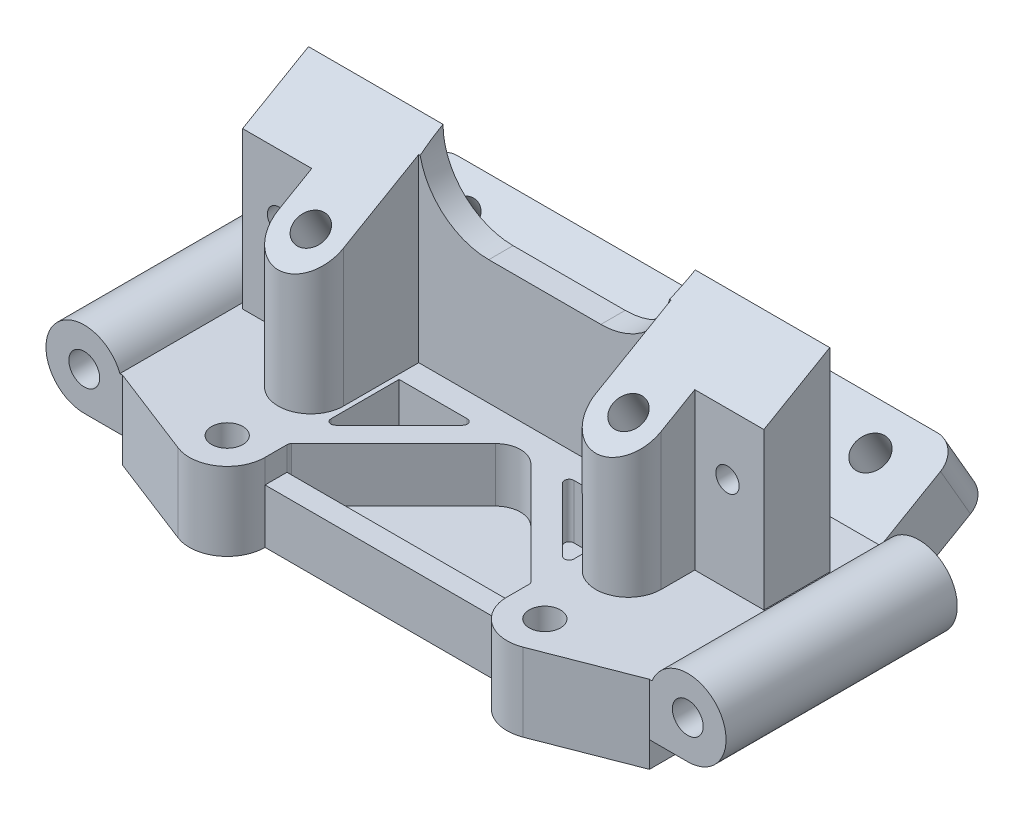
SolidWorks part; units mm, degrees
ref_plane "Front Plane" through (0, 0, 0) normal (0, 0, 1) x (1, 0, 0)
ref_plane "Top Plane" through (0, 0, 0) normal (0, 1, 0) x (1, 0, 0)
ref_plane "Right Plane" through (0, 0, 0) normal (1, 0, 0) x (0, 0, -1)
sketch "Sketch1" plane through (0, 0, 0) normal (0, 1, 0) x (1, 0, 0)
  line L0 (28.2, 0) -> (0, 0)
  line L1 (28.2, 0) -> (28.2, -24.75)
  line L2 (28.2, -24.75) -> (18.4645, -28.5259)
  line L3 (12.95, -24.75) -> (0, -24.75)
  line L4 (0, -24.75) -> (0, 0)
  arc A0 (12.95, -24.75) -> (18.4645, -28.5259) centre (17, -24.75) ccw
  circle A1 centre (17, -24.75) radius 1.675
  circle A2 centre (17, -9.75) radius 1.675
  point P9 (17, -28.8)
  point P11 (0, 0)
  dimension "D6" = 3.35
  dimension "D1" = 17
  dimension "D2" = 28.2
  dimension "D3" = 28.8
  dimension "D4" = 24.75
  dimension "D5" = 15
extrude "Boss-Extrude1" add sketch "Sketch1" along normal blind 8.35
sketch "Sketch2" plane through (0, 0, 0) normal (0, 0, -1) x (-1, 0, 0)
  line L0 (-28.2, 2.75) -> (-32.3, 2.75)
  line L1 (-28.2, 8.35) -> (-28.2, 0) construction
  line L2 (-28.2, 0) -> (0, 0) construction
  line L3 (-28.2, 2.75) -> (-28.2, 8.35)
  line L4 (-28.2, 8.35) -> (-28.4842, 8.35)
  arc A0 (-28.4842, 8.35) -> (-32.3, 2.75) centre (-32.3, 6.85) ccw
  circle A1 centre (-32.3, 6.85) radius 1.65
  point P5 (-36.4, 6.85)
  line M8 (-28.2, 8.35) -> (-28.2, 0)
  dimension "D1" = 8.2
  dimension "D3" = 3.3
  dimension "D2" = 2.75
extrude "Boss-Extrude2" add sketch "Sketch2" against normal up to vertex (24.75 mm away) contours L4 A0 L0 A1 M8
sketch "Sketch3" plane through (0, 8.35, 0) normal (0, 1, 0) x (1, 0, 0)
  line L0 (0, 0) -> (0, -24.75) construction
  line L1 (0, -5.15) -> (27.9, -5.15)
  line L2 (0, -5.15) -> (0, -12.2)
  line L3 (0, -12.2) -> (27.9, -12.2)
  line L4 (27.9, -5.15) -> (27.9, -12.2)
  line L5 (17, -12.2) -> (17, -15.8) construction
  line L6 (20.5, -12.2) -> (20.5, -15.8)
  line L7 (28.4842, 0) -> (0, 0) construction
  line L8 (13.5, -12.2) -> (13.5, -15.8)
  line L9 (13.5, -12.2) -> (13.5, -7.75)
  line L10 (13.5, -7.75) -> (0, -7.75)
  line L11 (0, -24.75) -> (12.95, -24.75) construction
  arc A0 (20.5, -12.2) -> (13.5, -12.2) centre (17, -12.2) ccw
  arc A1 (13.5, -15.8) -> (20.5, -15.8) centre (17, -15.8) ccw
  point P10 (17, -14)
  point P15 (17, -24.75)
  point P18 (17, -19.3)
  dimension "D1" = 7.05
  dimension "D2" = 12.2
  dimension "D3" = 27.9
  dimension "D4" = 17
  dimension "D5" = 14.15
  dimension "D6" = 17
  dimension "D7" = 7
extrude "Boss-Extrude3" add sketch "Sketch3" along normal blind 20.8
sketch "Sketch4" plane through (27.9, 0, 0) normal (1, 0, 0) x (0, 0, -1)
  line L0 (-5.15, 29.15) -> (-19.3, 20.9805)
  line L1 (-19.3, 20.9805) -> (-19.3, 29.15)
  line L2 (-19.3, 29.15) -> (-5.15, 29.15)
  line L3 (-19.3, 29.15) -> (-19.3, 8.35) construction
  point P5 (0, 0)
  dimension "D1" = 60
extrude "Cut-Extrude1" cut sketch "Sketch4" against normal through all
sketch "Sketch5" plane through (0, 0, 5.15) normal (0, 0, -1) x (-1, 0, 0)
  line L1 (0, 29.15) -> (-27.9, 29.15) construction
  line L2 (-6, 21.65) -> (0, 21.65)
  line L4 (0, 21.65) -> (0, 29.15)
  line L5 (0, 29.15) -> (-13.5, 29.15)
  arc A0 (-13.5, 29.15) -> (-6, 21.65) centre (-6, 29.15) ccw
  point P7 (0, 0)
  point P10 (0, 0)
  dimension "D1" = 7.5
  dimension "D2" = 7.5
  dimension "D3" = 13.5
extrude "Cut-Extrude2" cut sketch "Sketch5" against normal through all
sketch "Sketch6" plane through (0, 24.0925, 13.9098) normal (0, 0.866, 0.5) x (1, 0, 0)
  circle A0 centre (17, -2.1826) radius 1.675
  ellipse E0 centre (17, -2.1826) end of major axis (17, -6.224) minor radius 3.5 (13.5, -2.1826) -> (20.5, -2.1826) ccw construction
  dimension "D1" = 3.35
extrude "Cut-Extrude3" cut sketch "Sketch6" against normal blind 10
sketch "Sketch7" plane through (0, 0, 5.15) normal (0, 0, -1) x (-1, 0, 0)
  line L0 (0, 21.65) -> (0, 8.35) construction
  line L1 (-28.2, 0) -> (0, 0) construction
  circle A0 centre (-24, 18.5) radius 1.25
  dimension "D3" = 2.5
  dimension "D1" = 24
  dimension "D2" = 18.5
extrude "Cut-Extrude4" cut sketch "Sketch7" against normal through all
sketch "Sketch8" plane through (0, 8.35, 0) normal (0, 1, 0) x (1, 0, 0)
  line L0 (13, -10.35) -> (13, -17.6429)
  line L1 (12.1464, -17.9964) -> (5.3536, -11.2036)
  line L2 (5.7071, -10.35) -> (13, -10.35)
  line L3 (0, -24.75) -> (12.95, -24.75) construction
  line L4 (0, -7.75) -> (0, -24.75) construction
  line L5 (1.8879, -11.132) -> (12.8036, -22.0477)
  line L6 (12.95, -22.4012) -> (12.95, -24.75)
  line L7 (12.95, -24.75) -> (0, -24.75)
  line L8 (0, -24.75) -> (0, -10.35)
  arc A1 (13, -17.6429) -> (12.1464, -17.9964) centre (12.5, -17.6429) cw
  arc A2 (5.3536, -11.2036) -> (5.7071, -10.35) centre (5.7071, -10.85) cw
  arc A3 (1.8879, -11.132) -> (0, -10.35) centre (0, -13.0198) ccw
  arc A4 (12.8036, -22.0477) -> (12.95, -22.4012) centre (12.45, -22.4012) cw
  point P9 (13, -18.85)
  dimension "D4" = 0.5
  dimension "D5" = 2.4
  dimension "D6" = 0.5
  dimension "D1" = 14.4
  dimension "D2" = 13
  dimension "D3" = 8.5
extrude "Cut-Extrude5" cut sketch "Sketch8" against normal blind 5.8
sketch "Sketch9" plane through (0, 2.55, 0) normal (0, 1, 0) x (1, 0, 0)
  line L0 (12.95, -24.75) -> (12.95, -22.4012) construction
  line L1 (0, -24.75) -> (12.95, -24.75)
  line L2 (0, -24.75) -> (0, -22.4012)
  line L3 (0, -22.4012) -> (12.95, -22.4012)
  line L4 (12.95, -24.75) -> (12.95, -22.4012)
  point P7 (0, 0)
  point P8 (12.5, -21.9512)
extrude "Boss-Extrude4" add sketch "Sketch9" along normal blind 3.24
sketch "Sketch10" plane through (0, 0, 0) normal (-1, 0, 0) x (0, 0, 1)
  line L0 (0, 8.35) -> (-8.5696, 13.2977)
  line L1 (-8.5696, 13.2977) -> (-11.7754, 7.745)
  line L2 (-11.7754, 7.745) -> (-3.1152, 2.745)
  line L3 (-3.1152, 2.745) -> (-4.7, 0)
  line L4 (-4.7, 0) -> (0, 0)
  line L8 (12.2, 25.0797) -> (5.15, 29.15) construction
  line L20 (22.4012, 2.55) -> (10.35, 2.55)
  line L21 (10.35, 2.55) -> (10.35, 8.35)
  line L22 (10.35, 8.35) -> (7.75, 8.35)
  line L23 (7.75, 8.35) -> (7.75, 21.65)
  line L24 (7.75, 21.65) -> (5.15, 21.65)
  line L25 (5.15, 21.65) -> (5.15, 8.35)
  line L26 (5.15, 8.35) -> (0, 8.35)
  line L27 (0, 8.35) -> (0, 0)
  line L28 (0, 0) -> (24.75, 0)
  line L29 (24.75, 0) -> (24.75, 5.79)
  line L30 (24.75, 5.79) -> (22.4012, 5.79)
  line L31 (22.4012, 5.79) -> (22.4012, 2.55)
  line L39 (0, 8.35) -> (0, 0)
  point P3 (-12.4855, 10.1871)
  point P10 (-13.2546, 6.9461)
  dimension "D1" = 4.7
  dimension "D2" = 27
  dimension "D4" = 10
  dimension "D5" = 0
extrude "Boss-Extrude5" add sketch "Sketch10" against normal up to surface (28.2 mm away) up to face at (28.2, 1.375, 12.375)
fillet "Fillet1" radius 2.5 1 edges at (28.2, 10.5213, -10.1725)
sketch "Sketch11" plane through (0, 0.7098, 0.4098) normal (0, -0.866, -0.5) x (1, 0, 0)
  line L1 (25.7, -14.0703) -> (0, -14.0703) construction
  line L2 (0, -14.0703) -> (0, -4.0703) construction
  circle A0 centre (0, -10.0703) radius 1.75
  circle A1 centre (22, -10.0703) radius 1.75
  point P6 (0, 0)
  point P7 (0, 0)
  point P8 (19.4878, -9.9478)
  dimension "D2" = 3.5
  dimension "D1" = 22
  dimension "D3" = 4
extrude "Cut-Extrude6" cut sketch "Sketch11" against normal up to surface (6.4117 mm away) up to face at (16.5236, 11.1204, -4.7984)
sketch "Sketch12" plane through (0, 0.7098, 0.4098) normal (0, -0.866, -0.5) x (1, 0, 0)
  line L1 (25.8, -6.4703) -> (0, -6.4703)
  line L2 (25.8, -11.5703) -> (25.8, -6.4703)
  line L3 (3.8292, -11.6703) -> (25.7, -11.6703)
  line L4 (3.8292, -11.6703) -> (3.8292, -11.6703)
  line L5 (0, -11.8203) -> (0, -14.0703)
  line L6 (0, -14.0703) -> (25.7, -14.0703)
  line L7 (28.2, -11.5703) -> (28.2, -4.0703)
  line L8 (28.2, -4.0703) -> (0, -4.0703)
  line L9 (0, -4.0703) -> (0, -8.3203)
  line L10 (0, -11.8203) -> (0, -14.0703)
  line L11 (0, -14.0703) -> (25.7, -14.0703)
  line L12 (28.2, -11.5703) -> (28.2, -4.0703)
  line L13 (28.2, -4.0703) -> (0, -4.0703)
  line L14 (0, -4.0703) -> (0, -8.3203)
  line L15 (25.8, -6.4703) -> (2.4, -6.4703) construction
  line L16 (2.4, -6.4703) -> (2.4, -6.6847) construction
  arc A1 (3.8292, -11.6703) -> (2.0646, -6.4703) centre (0, -10.0703) ccw
  arc A2 (0, -11.8203) -> (0, -8.3203) centre (0, -10.0703) ccw
  arc A3 (25.7, -14.0703) -> (28.2, -11.5703) centre (25.7, -11.5703) ccw
  arc A4 (0, -11.8203) -> (0, -8.3203) centre (0, -10.0703) ccw
  arc A5 (25.7, -14.0703) -> (28.2, -11.5703) centre (25.7, -11.5703) ccw
  circle A6 centre (22, -10.0703) radius 4.15
  circle A7 centre (22, -10.0703) radius 4.15
  arc A8 (25.7, -11.6703) -> (25.8, -11.5703) centre (25.7, -11.5703) ccw
  arc A9 (3.8292, -11.6703) -> (2.4, -6.6847) centre (0, -10.0703) ccw construction
  dimension "D1" = 0
  dimension "D2" = 2.4
  dimension "D3" = 2.4
extrude "Cut-Extrude7" cut sketch "Sketch12" against normal blind 3.13 contours A7 L1 A1 L3
sketch "Sketch13" plane through (0, 7.0352, -12.1853) normal (0, 0.5, -0.866) x (-1, 0, 0)
  line L0 (-25.7, 7.2313) -> (0, 7.2313) construction
  line L1 (-18.68, 7.2313) -> (-3, 7.2313)
  line L2 (-18.68, 7.2313) -> (-18.68, 12.2313)
  line L3 (-18.68, 12.2313) -> (-3, 12.2313)
  line L4 (-3, 7.2313) -> (-3, 12.2313)
  point P6 (0, 7.2313)
  point P7 (0, 0)
  point P8 (0, 0)
  dimension "D1" = 15.68
  dimension "D2" = 3
  dimension "D3" = 5
extrude "Cut-Extrude8" cut sketch "Sketch13" against normal up to surface (15.842 mm away)
mirror "Mirror1" about plane through (0, 8.35, 24.75) normal (1, 0, 0) of bodies 114 112
